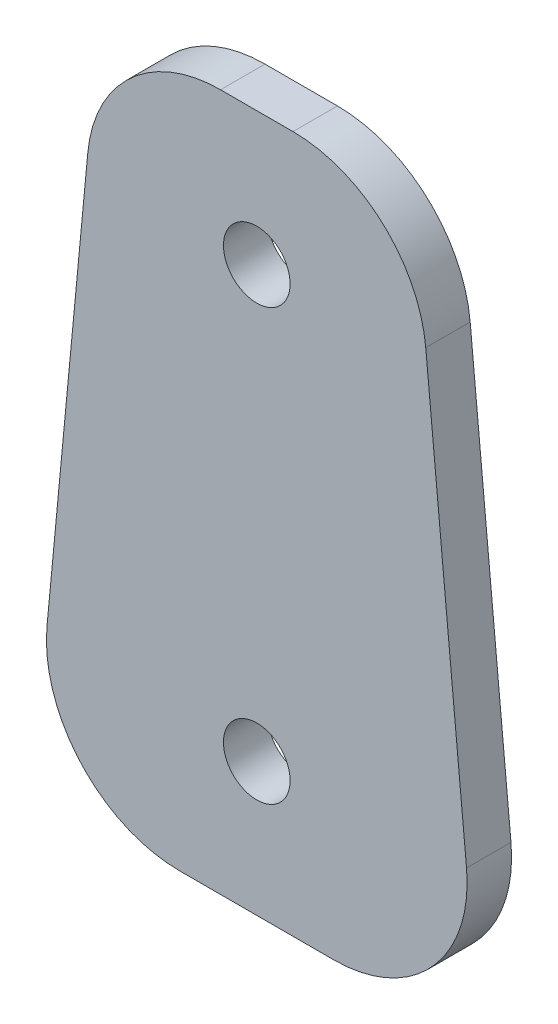
SolidWorks part; units mm, degrees
ref_plane "Front Plane" through (0, 0, 0) normal (0, 0, 1) x (1, 0, 0)
ref_plane "Top Plane" through (0, 0, 0) normal (0, 1, 0) x (1, 0, 0)
ref_plane "Right Plane" through (0, 0, 0) normal (1, 0, 0) x (0, 0, -1)
sketch "Sketch1" plane through (0, 0, 0) normal (0, 0, 1) x (1, 0, 0)
  line L1 (38.7964, 93.1012) -> (35.882, 123.8352)
  line L3 (11.743, 123.8352) -> (8.8286, 93.1012)
  line L4 (18.311, 82.677) -> (29.314, 82.677)
  line L5 (26.3995, 132.461) -> (21.2255, 132.461)
  arc A0 (21.2255, 132.461) -> (11.743, 123.8352) centre (21.2255, 122.936) ccw
  arc A1 (26.3995, 132.461) -> (35.882, 123.8352) centre (26.3995, 122.936) cw
  circle A2 centre (23.8125, 92.202) radius 2.3813
  circle A3 centre (23.8125, 122.936) radius 2.3813
  arc A4 (29.314, 82.677) -> (38.7964, 93.1012) centre (29.314, 92.202) ccw
  arc A5 (18.311, 82.677) -> (8.8286, 93.1012) centre (18.311, 92.202) cw
  dimension "D1" = 9.525
  dimension "D7" = 9.525
  dimension "D8" = 9.525
extrude "Boss-Extrude1" add sketch "Sketch1" along normal blind 3.175
